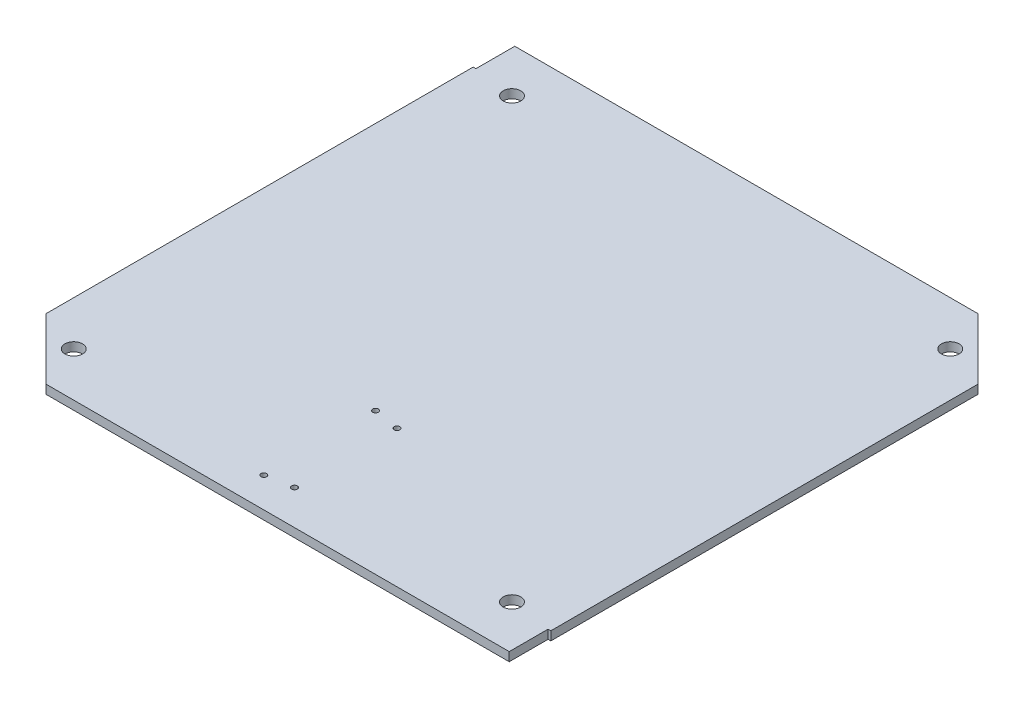
SolidWorks part; units mm, degrees
material "A-Glass Fiber"
ref_plane "Front Plane" through (0, 0, 0) normal (0, 0, 1) x (1, 0, 0)
ref_plane "Top Plane" through (0, 0, 0) normal (0, 1, 0) x (1, 0, 0)
ref_plane "Right Plane" through (0, 0, 0) normal (1, 0, 0) x (0, 0, -1)
sketch "Sketch1" plane through (0, 0, 0) normal (0, 1, 0) x (1, 0, 0)
  line L5 (-47.5, -36.5) -> (-36.5, -47.5)
  line L6 (-36.5, -47.5) -> (47, -47.5)
  line L8 (-47.5, -36.5) -> (-47.5, 40.5)
  line L10 (-47, 47.5) -> (36.5, 47.5)
  line L12 (47.5, -40.5) -> (47.5, 36.5)
  line L13 (-42, -42) -> (42, 42) construction
  line L14 (-47.5, 47.5) -> (47, -47) construction
  line L15 (36.5, 47.5) -> (47.5, 36.5)
  line L16 (-47.5, 40.5) -> (-47, 40.5)
  line L17 (-47, 40.5) -> (-47, 47.5)
  line L18 (47, -47.5) -> (47, -40.5)
  line L19 (47, -40.5) -> (47.5, -40.5)
  point P0 (0, 0)
  dimension "D1" = 95
  dimension "D2" = 95
  dimension "D3" = 11
  dimension "D4" = 11
  dimension "D5" = 11
  dimension "D6" = 11
  dimension "D7" = 0.5
  dimension "D8" = 7
  dimension "D9" = 0.5
  dimension "D10" = 7
extrude "Boss-Extrude1" add sketch "Sketch1" along normal blind 1.59
sketch "Sketch2" plane through (0, 1.59, 0) normal (0, 1, 0) x (1, 0, 0)
  line L0 (-47.5, 40.5) -> (-47.5, -36.5) construction
  line L1 (36.5, 47.5) -> (-47, 47.5) construction
  line L2 (47.5, -40.5) -> (47.5, 36.5) construction
  line L3 (-36.5, -47.5) -> (47, -47.5) construction
  circle A0 centre (-39.5, -39.5) radius 1.59
  circle A1 centre (-39.5, 39.5) radius 1.59
  circle A2 centre (39.5, 39.5) radius 1.59
  circle A3 centre (39.5, -39.5) radius 1.59
  circle A4 centre (-2.67, -21.93) radius 0.51
  circle A5 centre (2.03, -22.75) radius 0.51
  circle A6 centre (-2.67, -42.07) radius 0.51
  circle A7 centre (2.03, -41.24) radius 0.51
  point P24 (0, 0)
  point P25 (0, 0)
  point P26 (0, 0)
  dimension "D1" = 3.18
  dimension "D10" = 1.02
  dimension "D2" = 8
  dimension "D3" = 8
  dimension "D4" = 8
  dimension "D5" = 8
  dimension "D6" = 8
  dimension "D7" = 8
  dimension "D8" = 8
  dimension "D9" = 8
  dimension "D11" = 5.43
  dimension "D12" = 6.26
  dimension "D13" = 25.57
  dimension "D14" = 24.75
  dimension "D15" = 44.83
  dimension "D16" = 49.53
extrude "Cut-Extrude1" cut sketch "Sketch2" against normal through all
